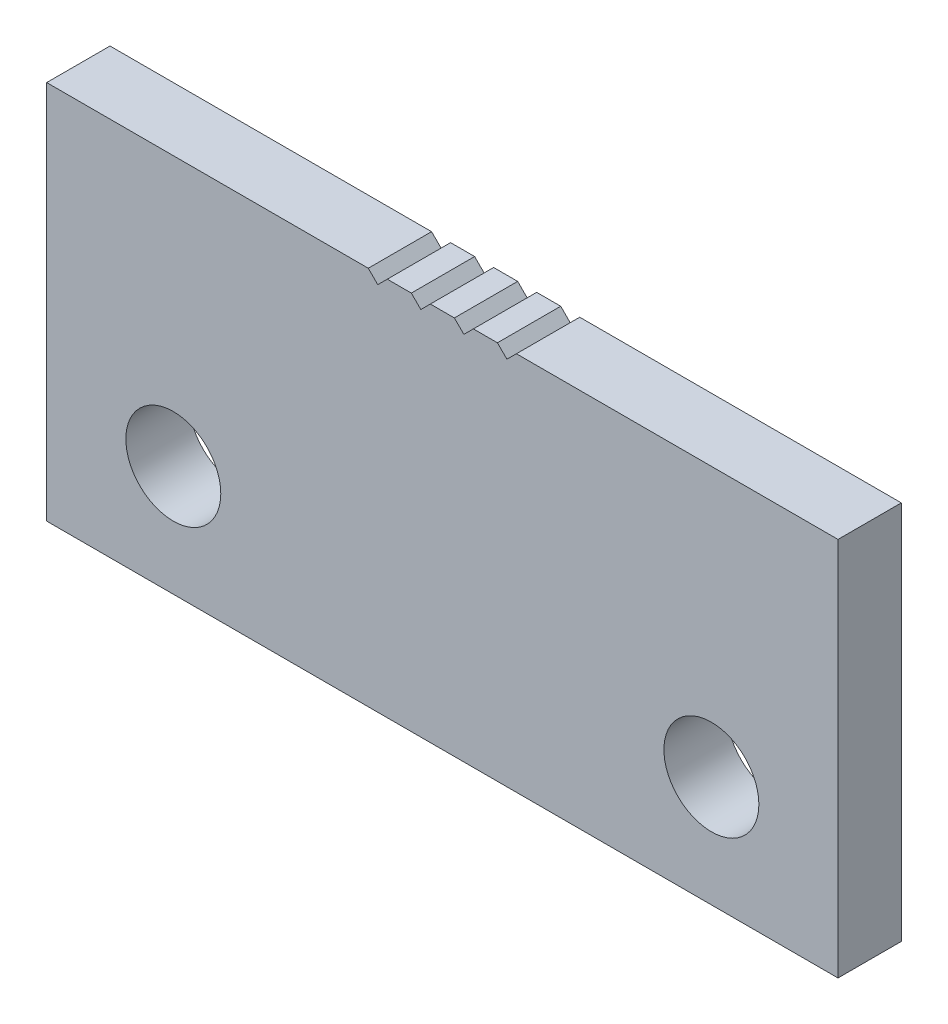
SolidWorks part; units mm, degrees
ref_plane "Front Plane" through (0, 0, 0) normal (0, 0, 1) x (1, 0, 0)
ref_plane "Top Plane" through (0, 0, 0) normal (0, 1, 0) x (1, 0, 0)
ref_plane "Right Plane" through (0, 0, 0) normal (1, 0, 0) x (0, 0, -1)
sketch "Sketch1" plane through (0, 0, 0) normal (0, 0, 1) x (1, 0, 0)
  line L0 (-2.34, 6) -> (-2.04, 5.7)
  line L1 (-12.5, -6) -> (12.5, -6)
  line L2 (-12.5, -6) -> (-12.5, 6)
  line L4 (12.5, -6) -> (12.5, 6)
  line L5 (-12.5, -6) -> (12.5, 6) construction
  line L6 (-12.5, 6) -> (12.5, -6) construction
  line L7 (-2.04, 5.7) -> (-1.74, 6)
  line L8 (-2.34, 6) -> (-2.34, 10.8354) construction
  line L9 (-2.34, 10.8354) -> (-1.74, 10.8354) construction
  line L10 (-1.74, 10.8354) -> (-1.74, 6) construction
  line L11 (-0.98, 6) -> (-0.68, 5.7)
  line L12 (-0.68, 5.7) -> (-0.38, 6)
  line L13 (-0.98, 6) -> (-0.98, 10.8354) construction
  line L14 (-0.98, 10.8354) -> (-0.38, 10.8354) construction
  line L15 (-0.38, 10.8354) -> (-0.38, 6) construction
  line L16 (0.38, 6) -> (0.68, 5.7)
  line L17 (0.68, 5.7) -> (0.98, 6)
  line L18 (0.38, 6) -> (0.38, 10.8354) construction
  line L19 (0.38, 10.8354) -> (0.98, 10.8354) construction
  line L20 (0.98, 10.8354) -> (0.98, 6) construction
  line L21 (1.74, 6) -> (2.04, 5.7)
  line L22 (2.04, 5.7) -> (2.34, 6)
  line L23 (1.74, 6) -> (1.74, 10.8354) construction
  line L24 (1.74, 10.8354) -> (2.34, 10.8354) construction
  line L25 (2.34, 10.8354) -> (2.34, 6) construction
  line L26 (-12.5, 6) -> (-2.34, 6)
  line L27 (-1.74, 6) -> (-0.98, 6)
  line L28 (-0.38, 6) -> (0.38, 6)
  line L29 (0.98, 6) -> (1.74, 6)
  line L30 (2.34, 6) -> (12.5, 6)
  line L31 (-2.34, 10.8354) -> (2.34, 10.8354) construction
  line L32 (8.5, -2.5) -> (-8.5, -2.5) construction
  line L33 (-8.5, -2.5) -> (-8.5, 2.5) construction
  circle A0 centre (8.5, -2.5) radius 1.5
  circle A1 centre (-8.5, -2.5) radius 1.5
  point P0 (0, 0)
  point P8 (-2.04, 10.8354)
  point P12 (0, 10.8354)
  point P13 (0, -6)
  point P37 (0, -2.5)
  point P38 (-8.5, 0)
  dimension "D6" = 3
  dimension "D1" = 25
  dimension "D2" = 12
  dimension "D3" = 0.6
  dimension "D4" = 0.3
  dimension "D7" = 1.36
  dimension "D8" = 4
  dimension "D9" = 8.5
  dimension "D5" = 4
extrude "Boss-Extrude1" add sketch "Sketch1" along normal blind 2
